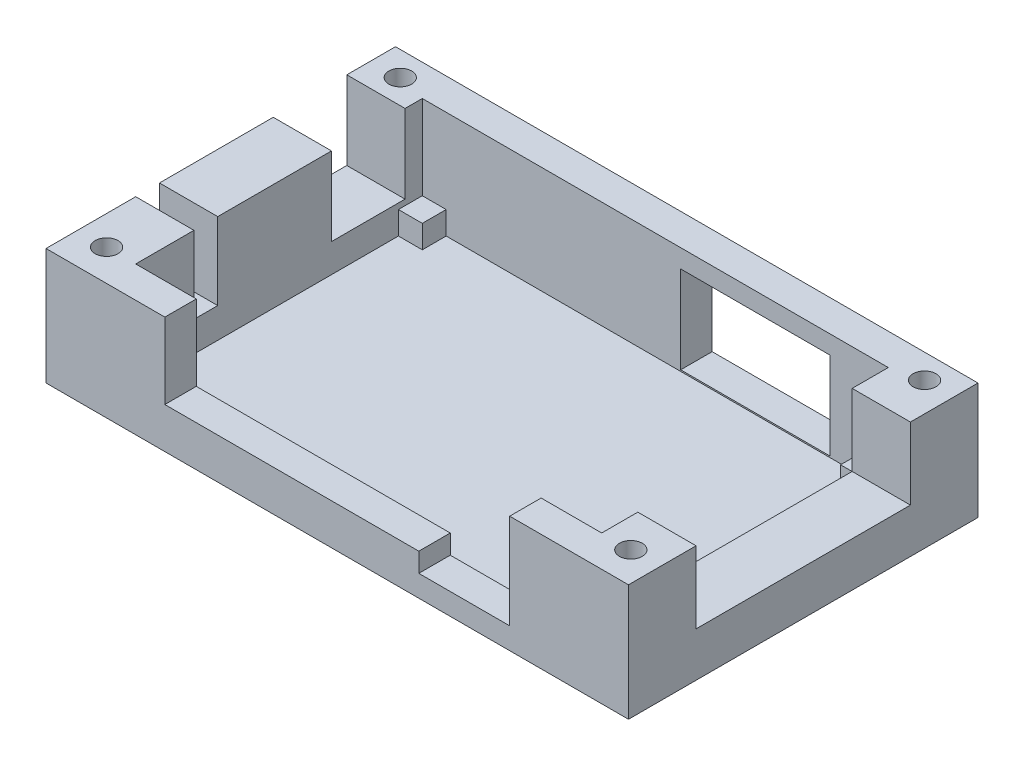
SolidWorks part; units mm, degrees
ref_plane "Alzado" through (0, 0, 0) normal (0, 0, 1) x (1, 0, 0)
ref_plane "Planta" through (0, 0, 0) normal (0, 1, 0) x (1, 0, 0)
ref_plane "Vista lateral" through (0, 0, 0) normal (1, 0, 0) x (0, 0, -1)
sketch "Croquis1" plane through (0, 0, 0) normal (0, 1, 0) x (1, 0, 0)
  line L5 (-63.5, -38.1) -> (63.5, -38.1)
  line L6 (-63.5, -38.1) -> (-63.5, 38.1)
  line L7 (-63.5, 38.1) -> (63.5, 38.1)
  line L8 (63.5, -38.1) -> (63.5, 38.1)
  line L9 (-63.5, -38.1) -> (63.5, 38.1) construction
  line L10 (-63.5, 38.1) -> (63.5, -38.1) construction
  point P0 (0, 0)
  dimension "D1" = 76.2
  dimension "D2" = 127
extrude "Saliente-Extruir1" add sketch "Croquis1" along normal blind 25.4
sketch "Croquis2" plane through (0, 25.4, 0) normal (0, 1, 0) x (1, 0, 0)
  line L1 (-50.8, -31.242) -> (50.8, -31.242)
  line L2 (-50.8, -31.242) -> (-50.8, 31.242)
  line L3 (-50.8, 31.242) -> (50.8, 31.242)
  line L4 (50.8, -31.242) -> (50.8, 31.242)
  line L5 (-50.8, -31.242) -> (50.8, 31.242) construction
  line L6 (-50.8, 31.242) -> (50.8, -31.242) construction
  point P0 (0, 0)
  dimension "D1" = 101.6
  dimension "D2" = 62.484
extrude "Cortar-Extruir1" cut sketch "Croquis2" against normal blind 23.368
sketch "Croquis3" plane through (63.5, 0, 0) normal (1, 0, 0) x (0, 0, -1)
  line L0 (-38.1, 25.4) -> (38.1, 25.4) construction
  line L1 (-23.368, 9.7115) -> (23.368, 9.7115)
  line L2 (-23.368, 9.7115) -> (-23.368, 25.4)
  line L3 (-23.368, 25.4) -> (23.368, 25.4)
  line L4 (23.368, 9.7115) -> (23.368, 25.4)
  line L5 (-23.368, 9.7115) -> (23.368, 25.4) construction
  line L6 (-23.368, 25.4) -> (23.368, 9.7115) construction
  line L7 (0, 0) -> (0, 17.5557) construction
  line L8 (-38.1, 0) -> (38.1, 0) construction
  point P0 (0, 17.5557)
  dimension "D1" = 15.6885
  dimension "D2" = 46.736
extrude "Cortar-Extruir2" cut sketch "Croquis3" against normal up to next
sketch "Croquis4" plane through (0, 0, 38.1) normal (0, 0, 1) x (1, 0, 0)
  line L0 (-63.5, 25.4) -> (63.5, 25.4) construction
  line L1 (-37.592, 8.89) -> (17.78, 8.89)
  line L2 (-37.592, 8.89) -> (-37.592, 25.4)
  line L3 (-37.592, 25.4) -> (37.592, 25.4)
  line L4 (37.592, 8.89) -> (37.592, 25.4)
  line L5 (-63.5, 25.4) -> (-63.5, 0) construction
  line L7 (0, 0) -> (0, 8.89) construction
  line L8 (-63.5, 0) -> (63.5, 0) construction
  line L10 (17.78, 4.699) -> (37.592, 4.699)
  line L11 (17.78, 4.699) -> (17.78, 8.89)
  line L13 (37.592, 4.699) -> (37.592, 8.89)
  point P0 (0, 0)
  point P17 (-83.5444, 8.89)
  dimension "D1" = 75.184
  dimension "D2" = 16.51
  dimension "D3" = 19.812
  dimension "D4" = 4.191
  dimension "D5" = 8.89
  dimension "D6" = 25.908
extrude "Cortar-Extruir3" cut sketch "Croquis4" against normal up to next
sketch "Croquis5" plane through (-63.5, 0, 0) normal (-1, 0, 0) x (0, 0, 1)
  line L1 (13.3604, 25.4) -> (18.542, 25.4)
  line L2 (13.3604, 25.4) -> (13.3604, 8.5979)
  line L3 (13.3604, 8.5979) -> (18.542, 8.5979)
  line L4 (18.542, 25.4) -> (18.542, 8.5979)
  line L5 (13.3604, 25.4) -> (18.542, 8.5979) construction
  line L6 (13.3604, 8.5979) -> (18.542, 25.4) construction
  line L7 (-38.1, 25.4) -> (38.1, 25.4) construction
  line L8 (31.242, 8.89) -> (31.242, 25.4) construction
  line L10 (-27.4828, 25.4) -> (-11.4478, 25.4)
  line L11 (-27.4828, 25.4) -> (-27.4828, 8.2804)
  line L12 (-27.4828, 8.2804) -> (-11.4478, 8.2804)
  line L13 (-11.4478, 25.4) -> (-11.4478, 8.2804)
  line L14 (-27.4828, 25.4) -> (-11.4478, 8.2804) construction
  line L15 (-27.4828, 8.2804) -> (-11.4478, 25.4) construction
  line L18 (-31.242, 2.032) -> (-31.242, 25.4) construction
  point P0 (15.9512, 16.999)
  point P9 (-19.4653, 16.8402)
  point P16 (-19.4652, 16.999)
  dimension "D1" = 5.1816
  dimension "D2" = 16.8021
  dimension "D3" = 12.7
  dimension "D4" = 16.035
  dimension "D5" = 17.1196
  dimension "D6" = 3.7592
extrude "Cortar-Extruir4" cut sketch "Croquis5" against normal up to next
sketch "Croquis6" plane through (0, 0, -38.1) normal (0, 0, -1) x (-1, 0, 0)
  line L1 (-38.1, 2.3368) -> (-5.5372, 2.3368)
  line L2 (-38.1, 2.3368) -> (-38.1, 21.3868)
  line L3 (-38.1, 21.3868) -> (-5.5372, 21.3868)
  line L4 (-5.5372, 2.3368) -> (-5.5372, 21.3868)
  line L5 (-38.1, 2.3368) -> (-5.5372, 21.3868) construction
  line L6 (-38.1, 21.3868) -> (-5.5372, 2.3368) construction
  line L7 (-63.5, 25.4) -> (63.5, 25.4) construction
  line L8 (-50.8, 2.032) -> (-50.8, 25.4) construction
  point P0 (-21.8186, 11.8618)
  point P5 (-27.5637, 11.7501)
  point P8 (-27.5987, 11.8618)
  dimension "D1" = 32.5628
  dimension "D2" = 19.05
  dimension "D3" = 4.0132
  dimension "D4" = 12.7
extrude "Cortar-Extruir5" cut sketch "Croquis6" against normal up to next
sketch "Croquis7" plane through (0, 25.4, 0) normal (0, 1, 0) x (1, 0, 0)
  line L0 (-57.15, -18.542) -> (-57.15, -38.1) construction
  line L1 (-50.8, -18.542) -> (-63.5, -18.542) construction
  line L2 (-63.5, -38.1) -> (-37.592, -38.1) construction
  line L3 (-50.8, -31.242) -> (-63.5, -31.242) construction
  line L4 (-63.5, -18.542) -> (-63.5, -38.1) construction
  line L5 (-57.15, 38.1) -> (-57.15, 27.4828) construction
  line L6 (63.5, 38.1) -> (-63.5, 38.1) construction
  line L7 (-50.8, 27.4828) -> (-63.5, 27.4828) construction
  line L8 (-63.5, 32.7914) -> (-44.1368, 32.7914)
  line L9 (-63.5, 38.1) -> (-63.5, 27.4828) construction
  line L10 (0, -18.542) -> (0, 21.3446) construction
  circle A0 centre (-57.15, -31.242) radius 2.4892
  circle A1 centre (-57.15, 32.7914) radius 2.4892
  circle A2 centre (57.15, -31.242) radius 2.4892
  circle A3 centre (57.15, 32.7914) radius 2.4892
  dimension "D1" = 4.9784
  dimension "D2" = 4.9784
extrude "Cortar-Extruir6" cut sketch "Croquis7" against normal through all contours L8 A1 | L8 A1 | A0 | A3 | A2
sketch "Croquis8" plane through (0, 2.032, 0) normal (0, 1, 0) x (1, 0, 0)
  line L1 (-50.8, 31.242) -> (-45.593, 31.242)
  line L2 (-50.8, 31.242) -> (-50.8, 26.035)
  line L3 (-50.8, 26.035) -> (-45.593, 26.035)
  line L4 (-45.593, 31.242) -> (-45.593, 26.035)
  line L5 (-50.8, -26.035) -> (-45.593, -26.035)
  line L6 (-50.8, -26.035) -> (-50.8, -31.242)
  line L7 (-50.8, -31.242) -> (-45.593, -31.242)
  line L8 (-45.593, -26.035) -> (-45.593, -31.242)
  line L9 (-50.8, -31.242) -> (50.8, -31.242) construction
  line L10 (-50.8, 31.242) -> (-50.8, -31.242) construction
  line L11 (0, -20.5557) -> (0, 21.919) construction
  line L12 (50.8, -31.242) -> (45.593, -31.242)
  line L13 (45.593, -26.035) -> (45.593, -31.242)
  line L14 (50.8, -26.035) -> (50.8, -31.242)
  line L15 (50.8, -26.035) -> (45.593, -26.035)
  line L16 (45.593, 31.242) -> (45.593, 26.035)
  line L17 (50.8, 26.035) -> (45.593, 26.035)
  line L18 (50.8, 31.242) -> (50.8, 26.035)
  line L19 (50.8, 31.242) -> (45.593, 31.242)
  dimension "D1" = 5.207
  dimension "D2" = 5.207
  dimension "D3" = 5.207
  dimension "D4" = 5.207
extrude "Saliente-Extruir2" add sketch "Croquis8" along normal blind 5.0038
sketch "Croquis9" plane through (0, 7.0358, 0) normal (0, 1, 0) x (1, 0, 0)
  circle A0 centre (-48.1965, 28.6385) radius 2.4892
  dimension "D1" = 4.9784
